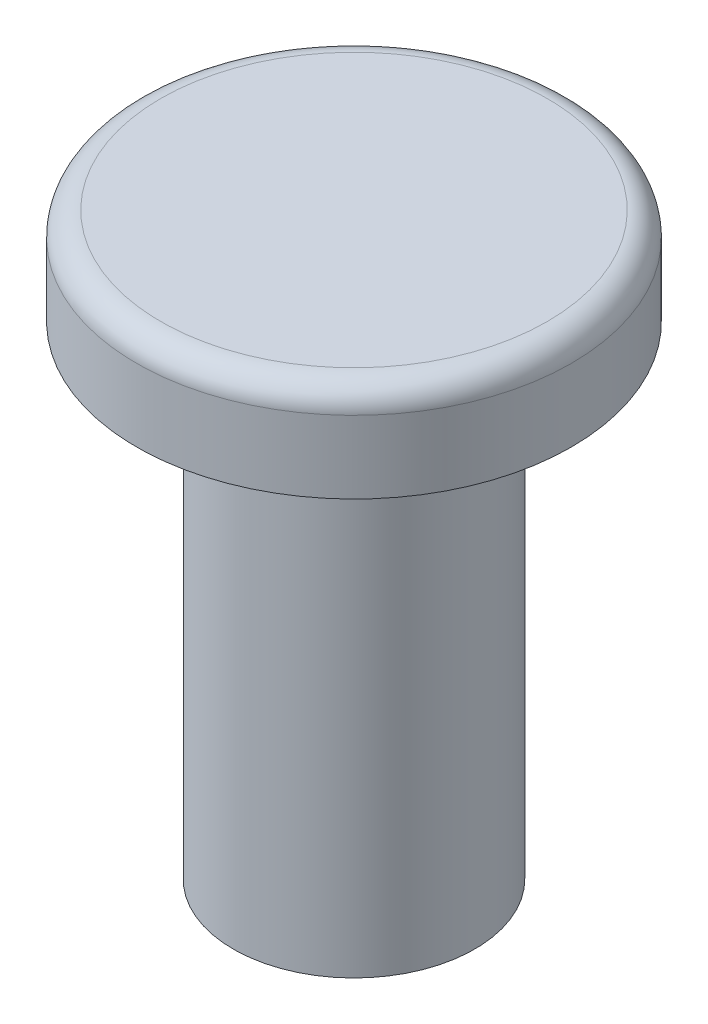
SolidWorks part; units mm, degrees
material "Cast Alloy Steel"
ref_plane "Front Plane" through (0, 0, 0) normal (0, 0, 1) x (1, 0, 0)
ref_plane "Top Plane" through (0, 0, 0) normal (0, 1, 0) x (1, 0, 0)
ref_plane "Right Plane" through (0, 0, 0) normal (1, 0, 0) x (0, 0, -1)
sketch "Sketch1" plane through (0, 0, 0) normal (0, 0, 1) x (1, 0, 0)
  line L0 (0, 5.802) -> (0, -0.198)
  line L1 (0, 5.802) -> (-2.25, 5.802)
  line L2 (-2.25, 5.802) -> (-2.25, 4.802)
  line L3 (-2.25, 4.802) -> (-1.25, 4.802)
  line L4 (-1.25, 4.802) -> (-1.25, -0.198)
  line L5 (-1.25, -0.198) -> (0, -0.198)
  dimension "D1" = 1.25
  dimension "D2" = 6
  dimension "D3" = 2.25
  dimension "D4" = 1
  dimension "D5" = 5.802
revolve "Revolve1" add sketch "Sketch1" angle 360 about L0
fillet "Fillet1" radius 0.25 1 edges at (-2.25, 5.802, 0)
